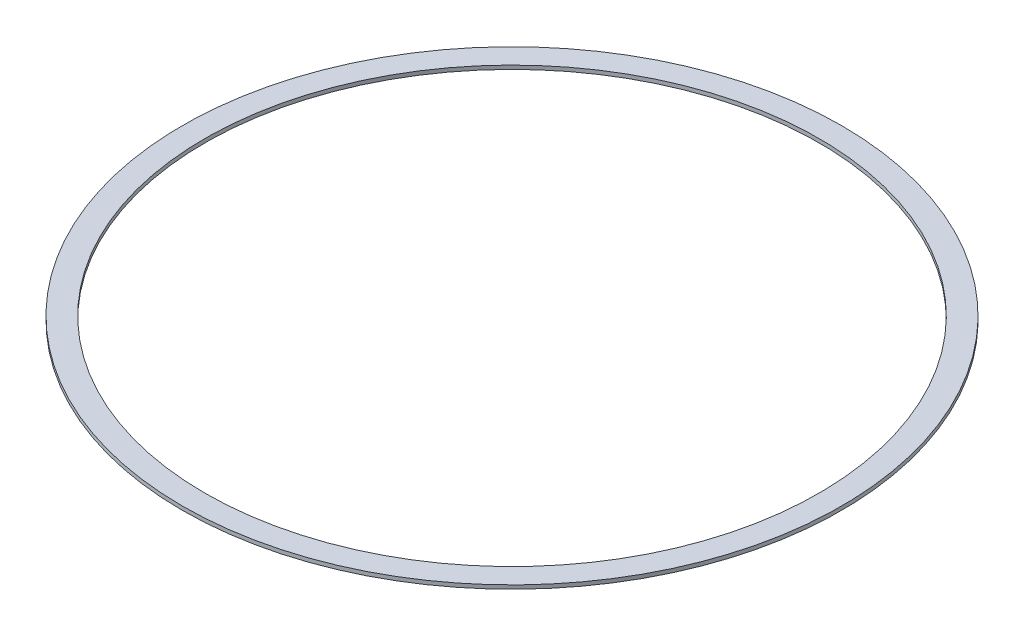
SolidWorks part; units mm, degrees
ref_plane "Front Plane" through (0, 0, 0) normal (0, 0, 1) x (1, 0, 0)
ref_plane "Top Plane" through (0, 0, 0) normal (0, 1, 0) x (1, 0, 0)
ref_plane "Right Plane" through (0, 0, 0) normal (1, 0, 0) x (0, 0, -1)
sketch "Sketch1" plane through (0, 0, 0) normal (0, 1, 0) x (1, 0, 0)
  circle A0 centre (0, 0) radius 206.8449
  circle A1 centre (0, 0) radius 221.9579
  dimension "D1" = 443.9158
  dimension "D2" = 413.6898
extrude "Boss-Extrude1" add sketch "Sketch1" along normal blind 2.54
ref_plane "Plane1" through (0, 1.27, 0) normal (0, 1, 0) x (1, 0, 0)
